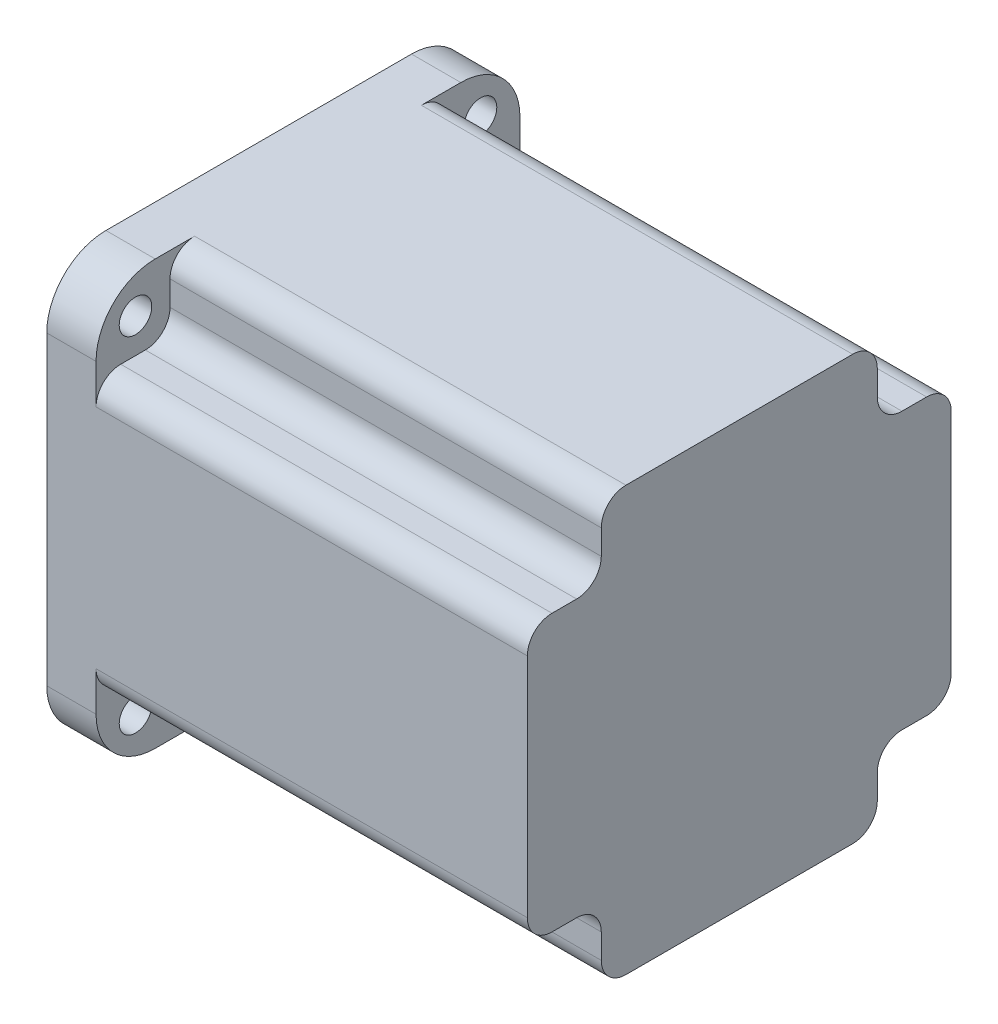
SolidWorks part; units mm, degrees
material "Stainless Steel (ferritic)"
ref_plane "Front Plane" through (0, 0, 0) normal (0, 0, 1) x (1, 0, 0)
ref_plane "Top Plane" through (0, 0, 0) normal (0, 1, 0) x (1, 0, 0)
ref_plane "Right Plane" through (0, 0, 0) normal (1, 0, 0) x (0, 0, -1)
sketch "Sketch1" plane through (0, 0, 0) normal (1, 0, 0) x (0, 0, -1)
  line L1 (-31, 43) -> (31, 43)
  line L2 (-43, 31) -> (-43, -31)
  line L3 (-31, -43) -> (31, -43)
  line L4 (43, 31) -> (43, -31)
  line L5 (-43, 43) -> (43, -43) construction
  line L6 (-43, -43) -> (43, 43) construction
  arc A0 (-31, 43) -> (-43, 31) centre (-31, 31) ccw
  arc A1 (-43, -31) -> (-31, -43) centre (-31, -31) ccw
  arc A2 (31, -43) -> (43, -31) centre (31, -31) ccw
  arc A3 (31, 43) -> (43, 31) centre (31, 31) cw
  point P0 (0, 0)
  dimension "D2" = 12
  dimension "D1" = 86
extrude "Boss-Extrude1" add sketch "Sketch1" along normal blind 97.5
sketch "Sketch2" plane through (0, 0, 0) normal (-1, 0, 0) x (0, 0, 1)
  circle A0 centre (0, 0) radius 36.5
  dimension "D1" = 73
extrude "Boss-Extrude2" add sketch "Sketch2" along normal blind 1.6
sketch "Sketch3" plane through (-1.6, 0, 0) normal (-1, 0, 0) x (0, 0, 1)
  circle A0 centre (0, 0) radius 7
  dimension "D1" = 14
extrude "Boss-Extrude4" add sketch "Sketch3" along normal blind 34 from surface at -1.6 starting at face at (0, 0, 36.5)
sketch "Sketch4" plane through (-34, 0, 0) normal (-1, 0, 0) x (0, 0, 1)
  line L0 (-4.899, 5) -> (4.899, 5)
  circle A1 centre (0, 0) radius 7 construction
  circle A2 centre (0, 0) radius 7
  arc A3 (4.899, 5) -> (-4.899, 5) centre (0, 0) ccw
  dimension ".5" = 5
  dimension "D1" = 0
extrude "Cut-Extrude1" cut sketch "Sketch4" against normal blind 24.8201
sketch "Sketch12" plane through (97.5, 0, 0) normal (1, 0, 0) x (0, 0, -1)
  line L0 (-28, 43) -> (28, 43)
  line L1 (31, 43) -> (-31, 43) construction
  line L2 (28, 43) -> (28, 28)
  line L3 (28, 28) -> (43, 28)
  line L4 (43, -31) -> (43, 31) construction
  line L5 (43, 28) -> (43, -28)
  line L6 (43, -28) -> (28, -28)
  line L7 (28, -28) -> (28, -43)
  line L8 (-31, -43) -> (31, -43) construction
  line L9 (28, -43) -> (-28, -43)
  line L10 (-28, -43) -> (-28, -28)
  line L11 (-28, -28) -> (-43, -28)
  line L12 (-43, 31) -> (-43, -31) construction
  line L13 (-43, -28) -> (-43, 28)
  line L14 (-43, 28) -> (-28, 28)
  line L15 (-28, 28) -> (-28, 43)
  point P13 (0, -43)
  point P21 (0, 43)
  point P22 (-43, 0)
  point P23 (43, 0)
  dimension "D1" = 15
  dimension "D2" = 15
extrude "Cut-Extrude2" cut sketch "Sketch12" against normal offset from surface (87.5 mm away) 10 flip side to cut up to face at (0, 0, 36.5)
hole_wizard "M6 Clearance Hole2" positions "Sketch9" profile "Sketch10" hole size "M6" standard "ANSI Metric" end condition through all
sketch "Sketch9" plane through (0, 0, 0) normal (-1, 0, 0) x (0, 0, 1)
  line L0 (-35, 35) -> (35, 35) construction
  line L1 (35, 35) -> (35, -35) construction
  point P0 (-35, 35)
  point P2 (35, 35)
  point P4 (35, -35)
  point P6 (-35, -35)
  point P19 (0, 35)
  point P20 (35, 0)
  dimension "D1" = 70
  dimension "D2" = 70
sketch "Sketch10" plane through (0, 35, -35) normal (0, 1, 0) x (0, 0, 1)
  line L0 (0, 0) -> (0, 97.5)
  line L1 (0, 97.5) -> (3.3, 97.5)
  line L2 (3.3, 97.5) -> (3.3, 0)
  line L5 (3.3, 0) -> (0, 0)
  line L11 (0, -6.35) -> (0, 107.95) construction
  dimension "Thru Hole Dia." = 6.6
  dimension "Thru Hole Depth" = 97.5
fillet "Fillet1" radius 5 12 edges at (53.75, 43, -28) (53.75, 28, 43) (53.75, 28, 28) (53.75, 43, 28) (53.75, 28, -43) (53.75, -28, -43) (53.75, -28, -28) (53.75, -43, -28) (53.75, -43, 28) (53.75, -28, 28) (53.75, -28, 43) (53.75, 28, -28)
chamfer "Chamfer1" distance 1 angle 45 1 edges at (-34, -7, 0)
